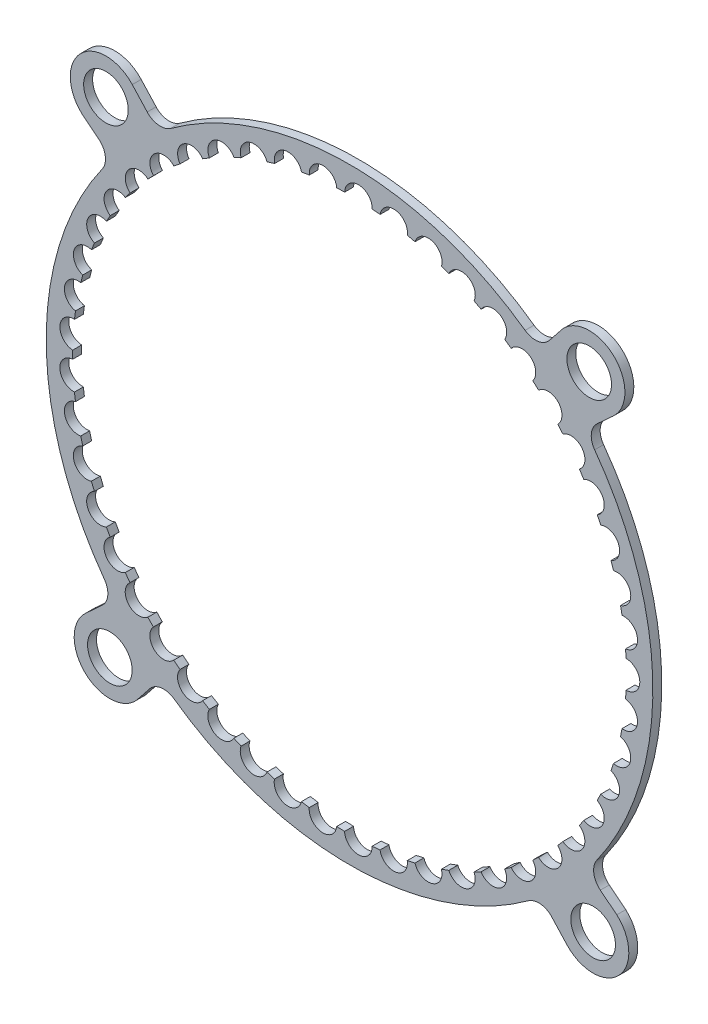
SolidWorks part; units mm, degrees
ref_plane "前视基准面" through (0, 0, 0) normal (0, 0, 1) x (1, 0, 0)
ref_plane "上视基准面" through (0, 0, 0) normal (0, 1, 0) x (1, 0, 0)
ref_plane "右视基准面" through (0, 0, 0) normal (1, 0, 0) x (0, 0, -1)
sketch "草图1" plane through (0, 0, 0) normal (0, 0, 1) x (1, 0, 0)
  line L0 (0, 0) -> (28.5, 0) construction
  line L1 (30.936, 2.4768) -> (30.9988, 1.4996) construction
  line L2 (30.9674, 1.9882) -> (32.4682, 2.0845) construction
  line L3 (30.936, -2.4768) -> (30.9988, -1.4996) construction
  line L4 (30.9674, -1.9882) -> (32.4682, -2.0845) construction
  line L5 (30.9674, -1.9882) -> (30.9956, -1.5491)
  line L6 (30.9674, 1.9882) -> (30.9962, 1.5394)
  line L7 (30.4589, -5.9319) -> (30.543, -5.5)
  line L8 (30.9674, -1.9882) -> (30.9386, -2.4369)
  line L9 (29.4503, -9.7782) -> (29.5889, -9.3606)
  line L10 (30.4589, -5.9319) -> (30.3729, -6.3732)
  line L11 (27.9581, -13.4639) -> (28.149, -13.0675)
  line L12 (29.4503, -9.7782) -> (29.3086, -10.2049)
  line L13 (26.0068, -16.9286) -> (26.2469, -16.5598)
  line L14 (27.9581, -13.4639) -> (27.763, -13.869)
  line L15 (23.6285, -20.1153) -> (23.9138, -19.7802)
  line L16 (26.0068, -16.9286) -> (25.7615, -17.3054)
  line L17 (20.8623, -22.9717) -> (21.188, -22.6759)
  line L18 (23.6285, -20.1153) -> (23.337, -20.4577)
  line L19 (17.7534, -25.4509) -> (18.1143, -25.1991)
  line L20 (20.8623, -22.9717) -> (20.5294, -23.274)
  line L21 (14.3531, -27.5122) -> (14.7432, -27.3087)
  line L22 (17.7534, -25.4509) -> (17.3846, -25.7081)
  line L23 (10.7171, -29.1217) -> (11.13, -28.9698)
  line L24 (14.3531, -27.5122) -> (13.9544, -27.7202)
  line L25 (6.9051, -30.2531) -> (7.334, -30.1552)
  line L26 (10.7171, -29.1217) -> (10.2951, -29.277)
  line L27 (2.9797, -30.8877) -> (3.4177, -30.8455)
  line L28 (6.9051, -30.2531) -> (6.4667, -30.3532)
  line L29 (-0.9946, -31.0152) -> (-0.5548, -31.0293)
  line L30 (2.9797, -30.8877) -> (2.5321, -30.9309)
  line L31 (-4.9526, -30.6334) -> (-4.5182, -30.7036)
  line L32 (-0.9946, -31.0152) -> (-1.444, -31.0008)
  line L33 (-8.8292, -29.7486) -> (-8.4074, -29.8737)
  line L34 (-4.9526, -30.6334) -> (-5.3965, -30.5616)
  line L35 (-12.5609, -28.3753) -> (-12.1585, -28.5534)
  line L36 (-8.8292, -29.7486) -> (-9.2603, -29.6206)
  line L37 (-16.0863, -26.5361) -> (-15.71, -26.7641)
  line L38 (-12.5609, -28.3753) -> (-12.9721, -28.1932)
  line L39 (-19.3476, -24.2611) -> (-19.0036, -24.5355)
  line L40 (-16.0863, -26.5361) -> (-16.4708, -26.3029)
  line L41 (-22.2912, -21.5878) -> (-21.9851, -21.9039)
  line L42 (-19.3476, -24.2611) -> (-19.6992, -23.9808)
  line L43 (-24.8688, -18.5601) -> (-24.6056, -18.9127)
  line L44 (-22.2912, -21.5878) -> (-22.604, -21.2648)
  line L45 (-27.038, -15.2275) -> (-26.8221, -15.6109)
  line L46 (-24.8688, -18.5601) -> (-25.1377, -18.1997)
  line L47 (-28.7633, -11.645) -> (-28.5982, -12.0528)
  line L48 (-27.038, -15.2275) -> (-27.2587, -14.8357)
  line L49 (-30.0163, -7.8712) -> (-29.9047, -8.2968)
  line L50 (-28.7633, -11.645) -> (-28.932, -11.2282)
  line L51 (-30.7764, -3.9682) -> (-30.7201, -4.4046)
  line L52 (-30.0163, -7.8712) -> (-30.1303, -7.4362)
  line L53 (-31.0311, 0) -> (-31.0311, -0.44)
  line L54 (-30.7764, -3.9682) -> (-30.8339, -3.5222)
  line L55 (-30.7764, 3.9682) -> (-30.8326, 3.5318)
  line L56 (-31.0311, 0) -> (-31.0311, 0.4497)
  line L57 (-30.0163, 7.8712) -> (-30.1279, 7.4456)
  line L58 (-30.7764, 3.9682) -> (-30.7189, 4.4142)
  line L59 (-28.7633, 11.645) -> (-28.9284, 11.2371)
  line L60 (-30.0163, 7.8712) -> (-29.9022, 8.3062)
  line L61 (-27.038, 15.2275) -> (-27.2539, 14.8441)
  line L62 (-28.7633, 11.645) -> (-28.5945, 12.0618)
  line L63 (-24.8688, 18.5601) -> (-25.1319, 18.2074)
  line L64 (-27.038, 15.2275) -> (-26.8173, 15.6193)
  line L65 (-22.2912, 21.5878) -> (-22.5973, 21.2717)
  line L66 (-24.8688, 18.5601) -> (-24.5998, 18.9204)
  line L67 (-19.3476, 24.2611) -> (-19.6916, 23.9868)
  line L68 (-22.2912, 21.5878) -> (-21.9784, 21.9108)
  line L69 (-16.0863, 26.5361) -> (-16.4626, 26.308)
  line L70 (-19.3476, 24.2611) -> (-18.996, 24.5415)
  line L71 (-12.5609, 28.3753) -> (-12.9632, 28.1972)
  line L72 (-16.0863, 26.5361) -> (-15.7018, 26.7692)
  line L73 (-8.8292, 29.7486) -> (-9.251, 29.6234)
  line L74 (-12.5609, 28.3753) -> (-12.1497, 28.5573)
  line L75 (-4.9526, 30.6334) -> (-5.3869, 30.5631)
  line L76 (-8.8292, 29.7486) -> (-8.3981, 29.8765)
  line L77 (-0.9946, 31.0152) -> (-1.4344, 31.0011)
  line L78 (-4.9526, 30.6334) -> (-4.5087, 30.7051)
  line L79 (2.9797, 30.8877) -> (2.5417, 30.93)
  line L80 (-0.9946, 31.0152) -> (-0.5452, 31.0296)
  line L81 (6.9051, 30.2531) -> (6.4761, 30.351)
  line L82 (2.9797, 30.8877) -> (3.4273, 30.8446)
  line L83 (10.7171, 29.1217) -> (10.3041, 29.2737)
  line L84 (6.9051, 30.2531) -> (7.3435, 30.1531)
  line L85 (14.3531, 27.5122) -> (13.963, 27.7157)
  line L86 (10.7171, 29.1217) -> (11.1391, 28.9664)
  line L87 (17.7534, 25.4509) -> (17.3926, 25.7026)
  line L88 (14.3531, 27.5122) -> (14.7518, 27.3042)
  line L89 (20.8623, 22.9717) -> (20.5365, 23.2675)
  line L90 (17.7534, 25.4509) -> (18.1222, 25.1936)
  line L91 (23.6285, 20.1153) -> (23.3433, 20.4503)
  line L92 (20.8623, 22.9717) -> (21.1951, 22.6694)
  line L93 (26.0068, 16.9286) -> (25.7668, 17.2973)
  line L94 (23.6285, 20.1153) -> (23.92, 19.7729)
  line L95 (27.9581, 13.4639) -> (27.7672, 13.8603)
  line L96 (26.0068, 16.9286) -> (26.2521, 16.5517)
  line L97 (29.4503, 9.7782) -> (29.3116, 10.1958)
  line L98 (27.9581, 13.4639) -> (28.1532, 13.0588)
  line L99 (30.4589, 5.9319) -> (30.3748, 6.3638)
  line L100 (29.4503, 9.7782) -> (29.592, 9.3514)
  line L101 (30.9674, 1.9882) -> (30.9392, 2.4273)
  line L102 (30.4589, 5.9319) -> (30.5449, 5.4905)
  line L103 (0, 0) -> (0, -28.5) construction
  line L105 (24.3531, -29.5669) -> (22.6815, -27.7408)
  line L106 (-29.5669, -24.3531) -> (-27.7408, -22.6815)
  line L109 (29.9564, -23.8723) -> (28.1103, -22.4011)
  line L112 (-23.8723, -29.9564) -> (-22.4011, -28.1103)
  line L115 (-24.3531, 29.5669) -> (-22.6815, 27.7408)
  line L121 (-29.9564, 23.8723) -> (-28.1103, 22.4011)
  line L122 (29.5669, 24.3531) -> (27.7408, 22.6815)
  line L123 (23.8723, 29.9564) -> (22.4011, 28.1103)
  circle A0 centre (0, 0) radius 34 construction
  circle A1 centre (0, 0) radius 32.535 construction
  circle A2 centre (31.035, 0) radius 1.5 construction
  circle A3 centre (30.7802, -3.9687) radius 1.5 construction
  circle A4 centre (30.02, -7.8722) radius 1.5 construction
  circle A5 centre (28.7669, -11.6464) radius 1.5 construction
  circle A6 centre (27.0414, -15.2294) radius 1.5 construction
  circle A7 centre (24.8719, -18.5624) radius 1.5 construction
  circle A8 centre (22.294, -21.5905) radius 1.5 construction
  circle A9 centre (19.35, -24.2641) radius 1.5 construction
  circle A10 centre (16.0883, -26.5394) radius 1.5 construction
  circle A11 centre (12.5625, -28.3788) radius 1.5 construction
  circle A12 centre (8.8303, -29.7523) radius 1.5 construction
  circle A13 centre (4.9532, -30.6372) radius 1.5 construction
  circle A14 centre (0.9947, -31.0191) radius 1.5 construction
  circle A15 centre (-2.9801, -30.8916) radius 1.5 construction
  circle A16 centre (-6.9059, -30.2569) radius 1.5 construction
  circle A17 centre (-10.7184, -29.1254) radius 1.5 construction
  circle A18 centre (-14.3549, -27.5156) radius 1.5 construction
  circle A19 centre (-17.7556, -25.454) radius 1.5 construction
  circle A20 centre (-20.8649, -22.9745) radius 1.5 construction
  circle A21 centre (-23.6315, -20.1178) radius 1.5 construction
  circle A22 centre (-26.0101, -16.9307) radius 1.5 construction
  circle A23 centre (-27.9616, -13.4656) radius 1.5 construction
  circle A24 centre (-29.4539, -9.7794) radius 1.5 construction
  circle A25 centre (-30.4627, -5.9326) radius 1.5 construction
  circle A26 centre (-30.9712, -1.9884) radius 1.5 construction
  circle A27 centre (-30.9712, 1.9884) radius 1.5 construction
  circle A28 centre (-30.4627, 5.9326) radius 1.5 construction
  circle A29 centre (-29.4539, 9.7794) radius 1.5 construction
  circle A30 centre (-27.9616, 13.4656) radius 1.5 construction
  circle A31 centre (-26.0101, 16.9307) radius 1.5 construction
  circle A32 centre (-23.6315, 20.1178) radius 1.5 construction
  circle A33 centre (-20.8649, 22.9745) radius 1.5 construction
  circle A34 centre (-17.7556, 25.454) radius 1.5 construction
  circle A35 centre (-14.3549, 27.5156) radius 1.5 construction
  circle A36 centre (-10.7184, 29.1254) radius 1.5 construction
  circle A37 centre (-6.9059, 30.2569) radius 1.5 construction
  circle A38 centre (-2.9801, 30.8916) radius 1.5 construction
  circle A39 centre (0.9947, 31.0191) radius 1.5 construction
  circle A40 centre (4.9532, 30.6372) radius 1.5 construction
  circle A41 centre (8.8303, 29.7523) radius 1.5 construction
  circle A42 centre (12.5625, 28.3788) radius 1.5 construction
  circle A43 centre (16.0883, 26.5394) radius 1.5 construction
  circle A44 centre (19.35, 24.2641) radius 1.5 construction
  circle A45 centre (22.294, 21.5905) radius 1.5 construction
  circle A46 centre (24.8719, 18.5624) radius 1.5 construction
  circle A47 centre (27.0414, 15.2294) radius 1.5 construction
  circle A48 centre (28.7669, 11.6464) radius 1.5 construction
  circle A49 centre (30.02, 7.8722) radius 1.5 construction
  circle A50 centre (30.7802, 3.9687) radius 1.5 construction
  circle A51 centre (0, 0) radius 31.035 construction
  arc A52 (30.9956, -1.5491) -> (32.535, 0) centre (30.9907, -0.0048) ccw
  arc A53 (30.9962, 1.5394) -> (32.535, 0) centre (30.9907, -0.0048) cw
  arc A54 (30.543, -5.5) -> (32.2679, -4.1605) centre (30.7357, -3.9678) ccw
  arc A55 (30.9386, -2.4369) -> (32.2679, -4.1605) centre (30.7357, -3.9678) cw
  arc A56 (29.5889, -9.3606) -> (31.4709, -8.2527) centre (29.976, -7.8656) ccw
  arc A57 (30.3729, -6.3732) -> (31.4709, -8.2527) centre (29.976, -7.8656) cw
  arc A58 (28.149, -13.0675) -> (30.1572, -12.2093) centre (28.724, -11.6343) ccw
  arc A59 (29.3086, -10.2049) -> (30.1572, -12.2093) centre (28.724, -11.6343) cw
  arc A60 (26.2469, -16.5598) -> (28.3484, -15.9655) centre (27.0005, -15.2119) ccw
  arc A61 (27.763, -13.869) -> (28.3484, -15.9655) centre (27.0005, -15.2119) cw
  arc A62 (23.9138, -19.7802) -> (26.074, -19.4595) centre (24.8335, -18.5398) ccw
  arc A63 (25.7615, -17.3054) -> (26.074, -19.4595) centre (24.8335, -18.5398) cw
  arc A64 (21.188, -22.6759) -> (23.3715, -22.634) centre (22.2588, -21.5632) ccw
  arc A65 (23.337, -20.4577) -> (23.3715, -22.634) centre (22.2588, -21.5632) cw
  arc A66 (18.1143, -25.1991) -> (20.2852, -25.4369) centre (19.3186, -24.2325) ccw
  arc A67 (20.5294, -23.274) -> (20.2852, -25.4369) centre (19.3186, -24.2325) cw
  arc A68 (14.7432, -27.3087) -> (16.8659, -27.8221) centre (16.0612, -26.504) ccw
  arc A69 (17.3846, -25.7081) -> (16.8659, -27.8221) centre (16.0612, -26.504) cw
  arc A70 (11.13, -28.9698) -> (13.1696, -29.7504) centre (12.5401, -28.3403) ccw
  arc A71 (13.9544, -27.7202) -> (13.1696, -29.7504) centre (12.5401, -28.3403) cw
  arc A72 (7.334, -30.1552) -> (9.2571, -31.1903) centre (8.8131, -29.7112) ccw
  arc A73 (10.2951, -29.277) -> (9.2571, -31.1903) centre (8.8131, -29.7112) cw
  arc A74 (3.4177, -30.8455) -> (5.1926, -32.118) centre (4.9414, -30.5943) ccw
  arc A75 (6.4667, -30.3532) -> (5.1926, -32.118) centre (4.9414, -30.5943) cw
  arc A76 (-0.5548, -31.0293) -> (1.0428, -32.5183) centre (0.9885, -30.975) ccw
  arc A77 (2.5321, -30.9309) -> (1.0428, -32.5183) centre (0.9885, -30.975) cw
  arc A78 (-4.5182, -30.7036) -> (-3.1241, -32.3847) centre (-2.9806, -30.8471) ccw
  arc A79 (-1.444, -31.0008) -> (-3.1241, -32.3847) centre (-2.9806, -30.8471) cw
  arc A80 (-8.4074, -29.8737) -> (-7.2397, -31.7193) centre (-6.9008, -30.2127) ccw
  arc A81 (-5.3965, -30.5616) -> (-7.2397, -31.7193) centre (-6.9008, -30.2127) cw
  arc A82 (-12.1585, -28.5534) -> (-11.2365, -30.5331) centre (-10.7076, -29.0822) ccw
  arc A83 (-9.2603, -29.6206) -> (-11.2365, -30.5331) centre (-10.7076, -29.0822) cw
  arc A84 (-15.71, -26.7641) -> (-15.0487, -28.8455) centre (-14.3387, -27.4741) ccw
  arc A85 (-12.9721, -28.1932) -> (-15.0487, -28.8455) centre (-14.3387, -27.4741) cw
  arc A86 (-19.0036, -24.5355) -> (-18.6138, -26.6843) centre (-17.7343, -25.415) ccw
  arc A87 (-16.4708, -26.3029) -> (-18.6138, -26.6843) centre (-17.7343, -25.415) cw
  arc A88 (-21.9851, -21.9039) -> (-21.8733, -24.0849) centre (-20.8387, -22.9385) ccw
  arc A89 (-19.6992, -23.9808) -> (-21.8733, -24.0849) centre (-20.8387, -22.9385) cw
  arc A90 (-24.6056, -18.9127) -> (-24.7736, -21.0901) centre (-23.6009, -20.0854) ccw
  arc A91 (-22.604, -21.2648) -> (-24.7736, -21.0901) centre (-23.6009, -20.0854) cw
  arc A92 (-26.8221, -15.6109) -> (-27.2672, -17.749) centre (-25.9756, -16.9025) ccw
  arc A93 (-25.1377, -18.1997) -> (-27.2672, -17.749) centre (-25.9756, -16.9025) cw
  arc A94 (-28.5982, -12.0528) -> (-29.313, -14.1164) centre (-27.9238, -13.442) ccw
  arc A95 (-27.2587, -14.8357) -> (-29.313, -14.1164) centre (-27.9238, -13.442) cw
  arc A96 (-29.9047, -8.2968) -> (-30.8775, -10.252) centre (-29.4135, -9.7609) ccw
  arc A97 (-28.932, -11.2282) -> (-30.8775, -10.252) centre (-29.4135, -9.7609) cw
  arc A98 (-30.7201, -4.4046) -> (-31.935, -6.2193) centre (-30.4202, -5.9194) ccw
  arc A99 (-30.1303, -7.4362) -> (-31.935, -6.2193) centre (-30.4202, -5.9194) cw
  arc A100 (-31.0311, -0.44) -> (-32.4682, -2.0845) centre (-30.9274, -1.9808) ccw
  arc A101 (-30.8339, -3.5222) -> (-32.4682, -2.0845) centre (-30.9274, -1.9808) cw
  arc A102 (-30.8326, 3.5318) -> (-32.4682, 2.0845) centre (-30.9268, 1.9904) ccw
  arc A103 (-31.0311, 0.4497) -> (-32.4682, 2.0845) centre (-30.9268, 1.9904) cw
  arc A104 (-30.1279, 7.4456) -> (-31.935, 6.2193) centre (-30.4183, 5.9289) ccw
  arc A105 (-30.7189, 4.4142) -> (-31.935, 6.2193) centre (-30.4183, 5.9289) cw
  arc A106 (-28.9284, 11.2371) -> (-30.8775, 10.252) centre (-29.4104, 9.77) ccw
  arc A107 (-29.9022, 8.3062) -> (-30.8775, 10.252) centre (-29.4104, 9.77) cw
  arc A108 (-27.2539, 14.8441) -> (-29.313, 14.1164) centre (-27.9196, 13.4507) ccw
  arc A109 (-28.5945, 12.0618) -> (-29.313, 14.1164) centre (-27.9196, 13.4507) cw
  arc A110 (-25.1319, 18.2074) -> (-27.2672, 17.749) centre (-25.9703, 16.9106) ccw
  arc A111 (-26.8173, 15.6193) -> (-27.2672, 17.749) centre (-25.9703, 16.9106) cw
  arc A112 (-22.5973, 21.2717) -> (-24.7736, 21.0901) centre (-23.5947, 20.0928) ccw
  arc A113 (-24.5998, 18.9204) -> (-24.7736, 21.0901) centre (-23.5947, 20.0928) cw
  arc A114 (-19.6916, 23.9868) -> (-21.8733, 24.0849) centre (-20.8315, 22.945) ccw
  arc A115 (-21.9784, 21.9108) -> (-21.8733, 24.0849) centre (-20.8315, 22.945) cw
  arc A116 (-16.4626, 26.308) -> (-18.6138, 26.6843) centre (-17.7264, 25.4205) ccw
  arc A117 (-18.996, 24.5415) -> (-18.6138, 26.6843) centre (-17.7264, 25.4205) cw
  arc A118 (-12.9632, 28.1972) -> (-15.0487, 28.8455) centre (-14.3301, 27.4786) ccw
  arc A119 (-15.7018, 26.7692) -> (-15.0487, 28.8455) centre (-14.3301, 27.4786) cw
  arc A120 (-9.251, 29.6234) -> (-11.2365, 30.5331) centre (-10.6986, 29.0855) ccw
  arc A121 (-12.1497, 28.5573) -> (-11.2365, 30.5331) centre (-10.6986, 29.0855) cw
  arc A122 (-5.3869, 30.5631) -> (-7.2397, 31.7193) centre (-6.8914, 30.2148) ccw
  arc A123 (-8.3981, 29.8765) -> (-7.2397, 31.7193) centre (-6.8914, 30.2148) cw
  arc A124 (-1.4344, 31.0011) -> (-3.1241, 32.3847) centre (-2.971, 30.848) ccw
  arc A125 (-4.5087, 30.7051) -> (-3.1241, 32.3847) centre (-2.971, 30.848) cw
  arc A126 (2.5417, 30.93) -> (1.0428, 32.5183) centre (0.9981, 30.9747) ccw
  arc A127 (-0.5452, 31.0296) -> (1.0428, 32.5183) centre (0.9981, 30.9747) cw
  arc A128 (6.4761, 30.351) -> (5.1926, 32.118) centre (4.9509, 30.5927) ccw
  arc A129 (3.4273, 30.8446) -> (5.1926, 32.118) centre (4.9509, 30.5927) cw
  arc A130 (10.3041, 29.2737) -> (9.2571, 31.1903) centre (8.8223, 29.7085) ccw
  arc A131 (7.3435, 30.1531) -> (9.2571, 31.1903) centre (8.8223, 29.7085) cw
  arc A132 (13.963, 27.7157) -> (13.1696, 29.7504) centre (12.5489, 28.3364) ccw
  arc A133 (11.1391, 28.9664) -> (13.1696, 29.7504) centre (12.5489, 28.3364) cw
  arc A134 (17.3926, 25.7026) -> (16.8659, 27.8221) centre (16.0695, 26.499) ccw
  arc A135 (14.7518, 27.3042) -> (16.8659, 27.8221) centre (16.0695, 26.499) cw
  arc A136 (20.5365, 23.2675) -> (20.2852, 25.4369) centre (19.3262, 24.2265) ccw
  arc A137 (18.1222, 25.1936) -> (20.2852, 25.4369) centre (19.3262, 24.2265) cw
  arc A138 (23.3433, 20.4503) -> (23.3715, 22.634) centre (22.2655, 21.5563) ccw
  arc A139 (21.1951, 22.6694) -> (23.3715, 22.634) centre (22.2655, 21.5563) cw
  arc A140 (25.7668, 17.2973) -> (26.074, 19.4595) centre (24.8393, 18.532) ccw
  arc A141 (23.92, 19.7729) -> (26.074, 19.4595) centre (24.8393, 18.532) cw
  arc A142 (27.7672, 13.8603) -> (28.3484, 15.9655) centre (27.0052, 15.2035) ccw
  arc A143 (26.2521, 16.5517) -> (28.3484, 15.9655) centre (27.0052, 15.2035) cw
  arc A144 (29.3116, 10.1958) -> (30.1572, 12.2093) centre (28.7277, 11.6253) ccw
  arc A145 (28.1532, 13.0588) -> (30.1572, 12.2093) centre (28.7277, 11.6253) cw
  arc A146 (30.3748, 6.3638) -> (31.4709, 8.2527) centre (29.9784, 7.8563) ccw
  arc A147 (29.592, 9.3514) -> (31.4709, 8.2527) centre (29.9784, 7.8563) cw
  arc A148 (30.9392, 2.4273) -> (32.2679, 4.1605) centre (30.7369, 3.9582) ccw
  arc A149 (30.5449, 5.4905) -> (32.2679, 4.1605) centre (30.7369, 3.9582) cw
  circle A201 centre (0, 0) radius 38.305 construction
  circle A202 centre (27.3036, -26.8661) radius 2.5
  circle A203 centre (27.3036, -26.8661) radius 4 construction
  arc A204 (24.3531, -29.5669) -> (29.9564, -23.8723) centre (27.3036, -26.8661) ccw
  arc A205 (-29.5669, -24.3531) -> (-23.8723, -29.9564) centre (-26.8661, -27.3036) ccw
  circle A206 centre (-26.8661, -27.3036) radius 2.5
  arc A207 (-24.3531, 29.5669) -> (-29.9564, 23.8723) centre (-27.3036, 26.8661) ccw
  circle A208 centre (-27.3036, 26.8661) radius 2.5
  arc A209 (29.5669, 24.3531) -> (23.8723, 29.9564) centre (26.8661, 27.3036) ccw
  circle A210 centre (26.8661, 27.3036) radius 2.5
  arc A211 (-19.6794, -27.7258) -> (20.0281, -27.475) centre (0, 0) ccw
  arc A212 (27.7258, -19.6794) -> (27.475, 20.0281) centre (0, 0) ccw
  arc A213 (19.6794, 27.7258) -> (-20.0281, 27.475) centre (0, 0) ccw
  arc A214 (-27.7258, 19.6794) -> (-27.475, -20.0281) centre (0, 0) ccw
  arc A215 (-22.4011, -28.1103) -> (-19.6794, -27.7258) centre (-20.837, -29.3567) cw
  arc A216 (22.6815, -27.7408) -> (20.0281, -27.475) centre (21.2062, -29.0912) ccw
  arc A217 (28.1103, -22.4011) -> (27.7258, -19.6794) centre (29.3567, -20.837) cw
  arc A218 (27.7408, 22.6815) -> (27.475, 20.0281) centre (29.0912, 21.2062) ccw
  arc A219 (22.4011, 28.1103) -> (19.6794, 27.7258) centre (20.837, 29.3567) cw
  arc A220 (-22.6815, 27.7408) -> (-20.0281, 27.475) centre (-21.2062, 29.0912) ccw
  arc A221 (-28.1103, 22.4011) -> (-27.7258, 19.6794) centre (-29.3567, 20.837) cw
  arc A222 (-27.7408, -22.6815) -> (-27.475, -20.0281) centre (-29.0912, -21.2062) ccw
  point P386 (21.4419, -26.3865)
  point P407 (26.5897, -21.1894)
  point P459 (-28.5, -28.5)
  dimension "D1" = 3
  dimension "D3" = 4
  dimension "D5" = 49
  dimension "D6" = 2
  dimension "D7" = 2
  dimension "D8" = 2
  dimension "D9" = 2
  dimension "D10" = 2
  dimension "D11" = 2
  dimension "D12" = 2
  dimension "D13" = 2
  dimension "D4" = 49
extrude "凸台-拉伸1" add sketch "草图1" along normal blind 1
